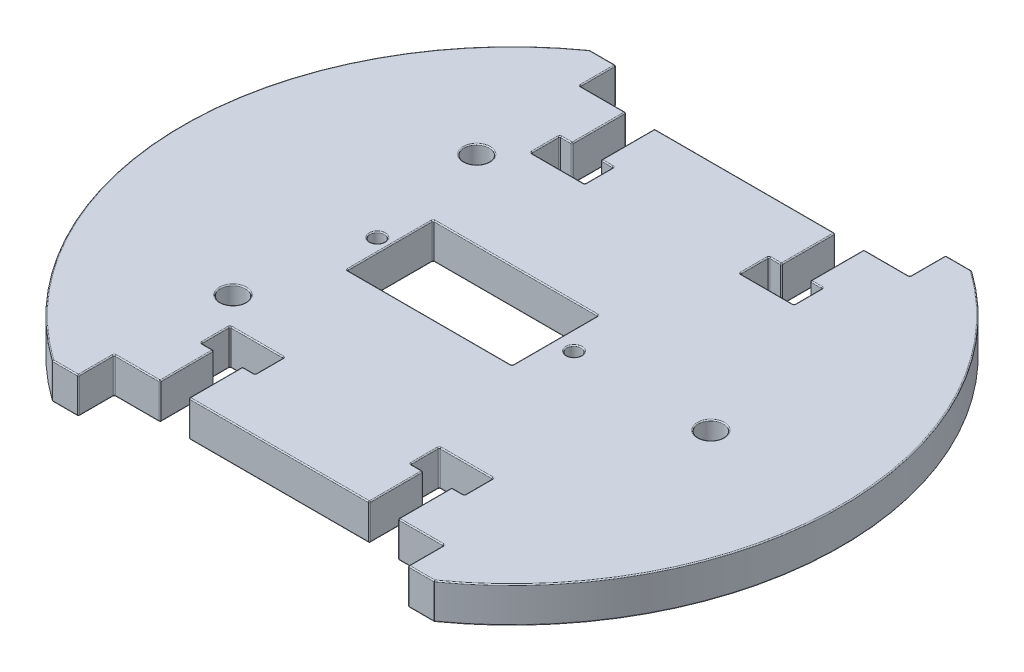
SolidWorks part; units mm, degrees
ref_plane "Front Plane" through (0, 0, 0) normal (0, 0, 1) x (1, 0, 0)
ref_plane "Top Plane" through (0, 0, 0) normal (0, 1, 0) x (1, 0, 0)
ref_plane "Right Plane" through (0, 0, 0) normal (1, 0, 0) x (0, 0, -1)
sketch "Sketch2" plane through (0, 0, 0) normal (0, 1, 0) x (1, 0, 0)
  line L0 (-26.6411, 37.5) -> (-23, 37.5)
  line L1 (23, 37.5) -> (26.6411, 37.5)
  line L3 (-23, 37.5) -> (-23, 32.5)
  line L4 (-23, 32.5) -> (23, 32.5)
  line L5 (23, 37.5) -> (23, 32.5)
  line L6 (0, 0) -> (-46, 0) construction
  line L7 (-26.6411, -37.5) -> (-23, -37.5)
  line L8 (-23, -37.5) -> (-23, -32.5)
  line L9 (-23, -32.5) -> (23, -32.5)
  line L10 (23, -37.5) -> (23, -32.5)
  line L11 (23, -37.5) -> (26.6411, -37.5)
  line L13 (-17, -6) -> (6, -6)
  line L14 (-17, -6) -> (-17, 6)
  line L15 (-17, 6) -> (6, 6)
  line L16 (6, -6) -> (6, 6)
  line L17 (-17, -6) -> (6, 6) construction
  line L18 (-17, 6) -> (6, -6) construction
  line L19 (-21.93, 17) -> (-21.93, -17) construction
  line L20 (0, 0) -> (27.75, 0) construction
  arc A0 (-26.6411, 37.5) -> (-26.6411, -37.5) centre (0, 0) ccw
  arc A1 (26.6411, -37.5) -> (26.6411, 37.5) centre (0, 0) ccw
  circle A2 centre (8.65, 0) radius 1
  circle A4 centre (-18.8, 0) radius 1
  circle A5 centre (27.75, 0) radius 1.75
  circle A6 centre (-21.93, -17) radius 1.75
  circle A7 centre (-21.93, 17) radius 1.75
  point P14 (0, 32.5)
  point P16 (-5.5, 0)
  point P21 (6, 0)
  point P28 (-17, 0)
  point P29 (-21.93, 0)
  point P34 (13.875, 0)
  dimension "D1" = 92
  dimension "D7" = 2
  dimension "D12" = 2
  dimension "D14" = 3.5
  dimension "D2" = 23
  dimension "D3" = 46
  dimension "D4" = 5
  dimension "D5" = 12
  dimension "D6" = 6
  dimension "D8" = 2.65
  dimension "D9" = 34
  dimension "D10" = 27.75
  dimension "D11" = 49.68
  dimension "D13" = 1.8
  dimension "D15" = 37.5
extrude "Boss-Extrude2" add sketch "Sketch2" along normal blind 5
sketch "Sketch3" plane through (0, 5, 0) normal (0, 1, 0) x (1, 0, 0)
  line L0 (23, 32.5) -> (-23, 32.5) construction
  line L1 (-16.6, 25) -> (-12.6, 25)
  line L2 (-16.6, 25) -> (-16.6, 32.5)
  line L3 (-16.6, 32.5) -> (-12.6, 32.5)
  line L4 (-12.6, 25) -> (-12.6, 32.5)
  line L5 (-16.6, 25) -> (-12.6, 32.5) construction
  line L6 (-16.6, 32.5) -> (-12.6, 25) construction
  line L7 (-17, 0) -> (0, 0) construction
  line L8 (-18.35, 21) -> (-10.85, 21)
  line L9 (-18.35, 21) -> (-18.35, 25)
  line L10 (-18.35, 25) -> (-10.85, 25)
  line L11 (-10.85, 21) -> (-10.85, 25)
  line L12 (-18.35, 21) -> (-10.85, 25) construction
  line L13 (-18.35, 25) -> (-10.85, 21) construction
  line L14 (-17, 6) -> (-17, -6) construction
  line L15 (0, -32.5) -> (0, 32.5) construction
  line L16 (18.35, 25) -> (10.85, 21) construction
  line L17 (18.35, 21) -> (10.85, 25) construction
  line L18 (16.6, 32.5) -> (12.6, 25) construction
  line L19 (16.6, 25) -> (12.6, 32.5) construction
  line L20 (10.85, 21) -> (10.85, 25)
  line L21 (18.35, 25) -> (10.85, 25)
  line L22 (18.35, 21) -> (18.35, 25)
  line L23 (18.35, 21) -> (10.85, 21)
  line L24 (12.6, 25) -> (12.6, 32.5)
  line L25 (16.6, 32.5) -> (12.6, 32.5)
  line L26 (16.6, 25) -> (16.6, 32.5)
  line L27 (16.6, 25) -> (12.6, 25)
  line L28 (16.6, -25) -> (12.6, -32.5) construction
  line L29 (16.6, -32.5) -> (12.6, -25) construction
  line L30 (18.35, -21) -> (10.85, -25) construction
  line L31 (18.35, -25) -> (10.85, -21) construction
  line L32 (-18.35, -25) -> (-10.85, -21) construction
  line L33 (-18.35, -21) -> (-10.85, -25) construction
  line L34 (-16.6, -32.5) -> (-12.6, -25) construction
  line L35 (-16.6, -25) -> (-12.6, -32.5) construction
  line L36 (16.6, -25) -> (12.6, -25)
  line L37 (16.6, -25) -> (16.6, -32.5)
  line L38 (16.6, -32.5) -> (12.6, -32.5)
  line L39 (12.6, -25) -> (12.6, -32.5)
  line L40 (18.35, -21) -> (10.85, -21)
  line L41 (18.35, -21) -> (18.35, -25)
  line L42 (18.35, -25) -> (10.85, -25)
  line L43 (10.85, -21) -> (10.85, -25)
  line L44 (-10.85, -21) -> (-10.85, -25)
  line L45 (-18.35, -25) -> (-10.85, -25)
  line L46 (-18.35, -21) -> (-18.35, -25)
  line L47 (-18.35, -21) -> (-10.85, -21)
  line L48 (-12.6, -25) -> (-12.6, -32.5)
  line L49 (-16.6, -32.5) -> (-12.6, -32.5)
  line L50 (-16.6, -25) -> (-16.6, -32.5)
  line L51 (-16.6, -25) -> (-12.6, -25)
  point P0 (-14.6, 28.75)
  point P7 (-14.6, 23)
  point P27 (14.6, 23)
  point P28 (14.6, 28.75)
  point P46 (14.6, -28.75)
  point P47 (14.6, -23)
  point P48 (-14.6, -23)
  point P49 (-14.6, -28.75)
  dimension "D1" = 6.4
  dimension "D2" = 4
  dimension "D3" = 7.5
  dimension "D4" = 4
  dimension "D5" = 7.5
extrude "Cut-Extrude1" cut sketch "Sketch3" against normal through all contours L2 L3 L4 L1 | L9 L10 L11 L8 | L24 L25 L26 L27 | L20 L21 L22 L23 | L46 L45 L44 L47 | L50 L49 L48 L51 | L43 L42 L41 L40 | L39 L38 L37 L36
fillet "Fillet1" radius 0.15 123 edges at (-16.6, 2.5, -25) (-16.6, 2.5, -32.5) (-12.6, 2.5, -32.5) (-12.6, 2.5, -25) (-16.6, 0, -28.75) (-12.6, 0, -28.75) (-16.6, 5, -28.75) (-12.6, 5, -28.75) (-18.35, 2.5, -25) (-10.85, 2.5, -25) (-10.85, 2.5, -21) (-17.475, 0, -25) (-11.725, 0, -25) (-10.85, 0, -23) (-14.6, 0, -21) (-18.35, 5, -23) (-17.475, 5, -25) (-11.725, 5, -25) (-10.85, 5, -23) (-14.6, 5, -21) (-10.85, 2.5, 21) (-18.35, 2.5, 25) (-18.35, 2.5, 21) (-17.475, 0, 25) (-11.725, 0, 25) (-10.85, 0, 23) (-14.6, 0, 21) (-18.35, 5, 23) (-17.475, 5, 25) (-11.725, 5, 25) (-10.85, 5, 23) (-14.6, 5, 21) (-12.6, 2.5, 32.5) (-16.6, 2.5, 32.5) (-16.6, 0, 28.75) (-12.6, 0, 28.75) (-16.6, 5, 28.75) (-12.6, 5, 28.75) (16.6, 2.5, 25) (12.6, 2.5, 25) (18.35, 2.5, 25) (10.85, 2.5, 25) (10.85, 2.5, 21) (18.35, 0, 23) (17.475, 0, 25) (11.725, 0, 25) (10.85, 0, 23) (14.6, 0, 21) (18.35, 5, 23) (17.475, 5, 25) (11.725, 5, 25) (10.85, 5, 23) (14.6, 5, 21) (16.6, 2.5, 32.5) (12.6, 0, 28.75) (16.6, 5, 28.75) (10.85, 5, -23) (11.725, 5, -25) (14.6, 0, -21) (10.85, 0, -23) (17.475, 0, -25) (18.35, 0, -23) (18.35, 2.5, -21) (18.35, 2.5, -25) (10.85, 2.5, -25) (10.85, 2.5, -21) (16.6, 5, -28.75) (12.6, 0, -28.75) (16.6, 0, -28.75) (16.6, 2.5, -25) (16.6, 2.5, -32.5) (12.6, 2.5, -32.5) (12.6, 2.5, -25) (-21.93, 0, -15.25) (-18.8, 0, 1) (-18.8, 5, 1) (27.75, 0, 1.75) (27.75, 5, 1.75) (8.65, 0, 1) (8.65, 5, 1) (6, 0, 0) (-5.5, 0, -6) (-5.5, 0, 6) (-5.5, 5, -6) (-17, 5, 0) (-5.5, 5, 6) (6, 2.5, 6) (-17, 2.5, 6) (6, 2.5, -6) (-46, 0, 0) (0, 0, 32.5) (-19.8, 0, 32.5) (23, 0, 35) (24.8206, 0, 37.5) (46, 0, 0) (24.8206, 0, -37.5) (23, 0, -35) (0, 0, -32.5) (-24.8206, 0, -37.5) (-46, 5, 0) (-24.8206, 5, 37.5) (-23, 5, 35) (0, 5, 32.5) (-19.8, 5, 32.5) (23, 5, 35) (24.8206, 5, 37.5) (46, 5, 0) (24.8206, 5, -37.5) (23, 5, -35) (-19.8, 5, -32.5) (0, 5, -32.5) (19.8, 5, -32.5) (-23, 5, -35) (-24.8206, 5, -37.5) (-23, 2.5, -37.5) (-23, 2.5, -32.5) (23, 2.5, -32.5) (23, 2.5, -37.5) (26.6411, 2.5, 37.5) (23, 2.5, 37.5) (23, 2.5, 32.5) (-23, 2.5, 32.5) (-26.6411, 2.5, 37.5)
